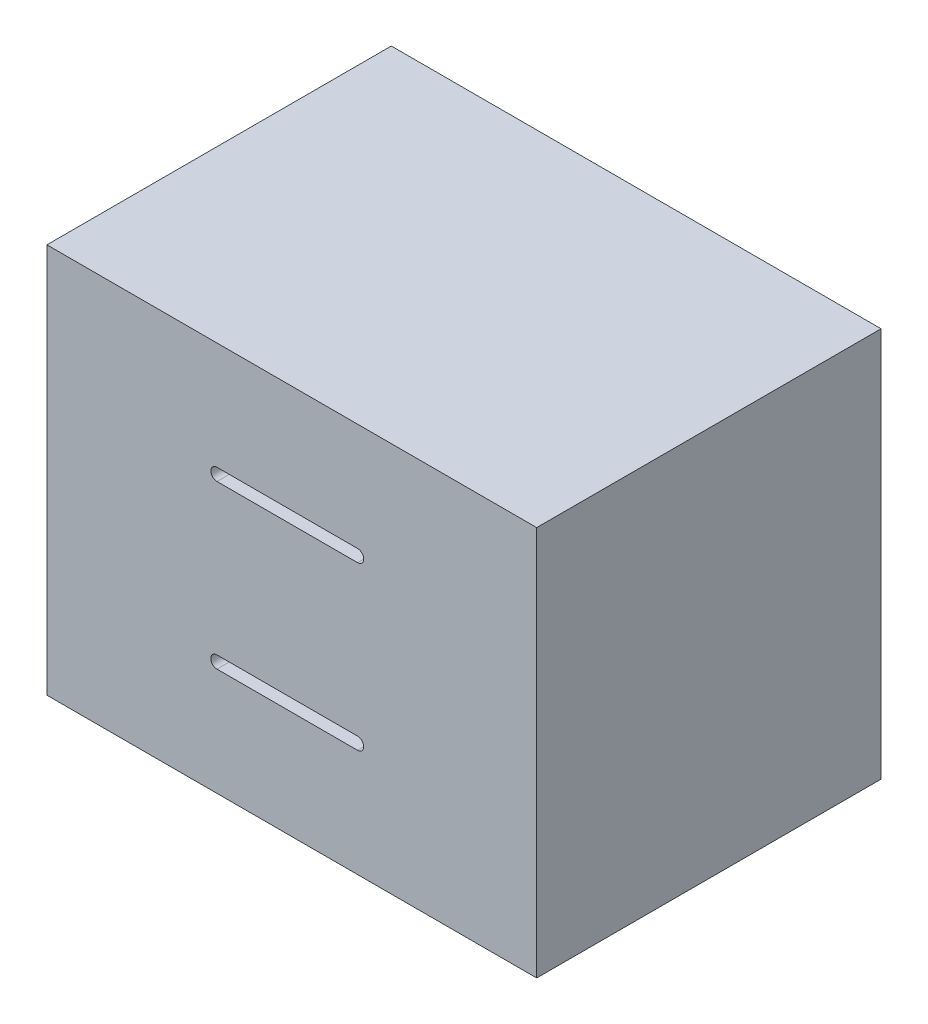
SolidWorks part; units mm, degrees
ref_plane "Front Plane" through (0, 0, 0) normal (0, 0, 1) x (1, 0, 0)
ref_plane "Top Plane" through (0, 0, 0) normal (0, 1, 0) x (1, 0, 0)
ref_plane "Right Plane" through (0, 0, 0) normal (1, 0, 0) x (0, 0, -1)
sketch "Sketch1" plane through (0, 0, 0) normal (0, 1, 0) x (1, 0, 0)
  line L1 (-26.9, -18.915) -> (26.9, -18.915)
  line L2 (-26.9, -18.915) -> (-26.9, 18.915)
  line L3 (-26.9, 18.915) -> (26.9, 18.915)
  line L4 (26.9, -18.915) -> (26.9, 18.915)
  line L5 (-26.9, -18.915) -> (26.9, 18.915) construction
  line L6 (-26.9, 18.915) -> (26.9, -18.915) construction
  point P0 (0, 0)
  dimension "D1" = 53.8
  dimension "D2" = 37.83
extrude "Boss-Extrude1" add sketch "Sketch1" along normal blind 42.85
sketch "Sketch2" plane through (0, 0, -18.915) normal (0, 0, -1) x (-1, 0, 0)
  line L0 (-7.225, 30.35) -> (8.225, 30.35) construction
  line L1 (-7.225, 31.025) -> (8.225, 31.025)
  line L2 (-7.225, 29.675) -> (8.225, 29.675)
  line L3 (-7.9, 42.85) -> (-7.9, 30.35) construction
  line L4 (-26.9, 42.85) -> (26.9, 42.85) construction
  line L5 (8.9, 30.35) -> (8.9, 42.85) construction
  line L6 (-26.9, 42.85) -> (-26.9, 0) construction
  line L7 (26.9, 42.85) -> (26.9, 0) construction
  line L8 (-7.225, 12.5) -> (8.225, 12.5) construction
  line L9 (-7.225, 13.175) -> (8.225, 13.175)
  line L10 (-7.225, 11.825) -> (8.225, 11.825)
  line L11 (0.5, 12.5) -> (0.5, 30.35) construction
  line L12 (0.5, 21.425) -> (-26.9, 21.425) construction
  arc A0 (-7.225, 31.025) -> (-7.225, 29.675) centre (-7.225, 30.35) ccw
  arc A1 (8.225, 29.675) -> (8.225, 31.025) centre (8.225, 30.35) ccw
  arc A2 (-7.225, 13.175) -> (-7.225, 11.825) centre (-7.225, 12.5) ccw
  arc A3 (8.225, 11.825) -> (8.225, 13.175) centre (8.225, 12.5) ccw
  point P2 (0.5, 30.35)
  point P19 (0.5, 12.5)
  point P28 (0.5, 29.675)
  point P29 (0.5, 13.175)
  dimension "D1" = 19
  dimension "D2" = 1.35
  dimension "D3" = 18
  dimension "D4" = 16.5
extrude "Cut-Extrude1" cut sketch "Sketch2" against normal blind 2
ref_plane "Plane1" through (0, 0, 0) normal (0, 0, -1) x (-1, 0, 0)
mirror "Mirror1" about plane through (0, 0, 0) normal (0, 0, -1) of "Cut-Extrude1"
